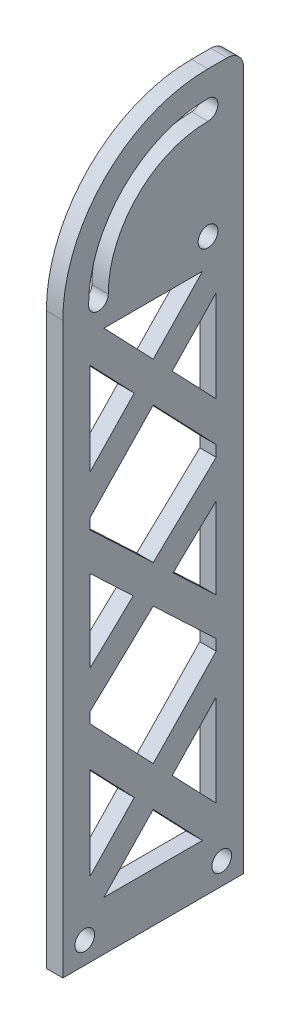
SolidWorks part; units mm, degrees
ref_plane "Front Plane" through (0, 0, 0) normal (0, 0, 1) x (1, 0, 0)
ref_plane "Top Plane" through (0, 0, 0) normal (0, 1, 0) x (1, 0, 0)
ref_plane "Right Plane" through (0, 0, 0) normal (1, 0, 0) x (0, 0, -1)
sketch "Sketch1" plane through (0, 0, 0) normal (1, 0, 0) x (0, 0, -1)
  line L0 (28, 103.9687) -> (33, 103.9687) construction
  line L1 (-14.1357, 103.9687) -> (0, 103.9687) construction
  line L2 (33, 103.9687) -> (33, 127.4687)
  line L3 (30, 130.4687) -> (26.5, 130.4687)
  line L4 (4, 4) -> (29, 4) construction
  line L5 (16.5, 4) -> (16.5, 0) construction
  line L7 (33, 103.9687) -> (33, 0)
  line L8 (33, 0) -> (0, 0)
  line L9 (0, 103.9687) -> (0, 0)
  circle A0 centre (4, 4) radius 1.5
  circle A1 centre (29, 4) radius 1.5
  circle A2 centre (26.5, 103.9687) radius 1.5
  arc A7 (0, 103.9687) -> (26.5, 130.4687) centre (26.5, 103.9687) cw
  arc A8 (33, 127.4687) -> (30, 130.4687) centre (30, 127.4687) ccw
  arc A9 (4.7, 103.9687) -> (26.5, 125.7687) centre (26.5, 103.9687) cw
  arc A10 (8.3, 103.9687) -> (26.5, 122.1687) centre (26.5, 103.9687) cw
  arc A11 (4.7, 103.9687) -> (8.3, 103.9687) centre (6.5, 103.9687) ccw
  arc A12 (26.5, 122.1687) -> (26.5, 125.7687) centre (26.5, 123.9687) ccw
  arc A13 (4.7, 103.9687) -> (26.5, 125.7687) centre (26.5, 103.9687) cw construction
  point P6 (0, 0)
  dimension "D1" = 3
  dimension "D2" = 3
  dimension "D4" = 3
  dimension "D6" = 4
  dimension "D12" = 3
  dimension "D9" = 3.6
  dimension "D11" = 20
  dimension "D3" = 4
  dimension "D5" = 100
  dimension "D10" = 5
  dimension "D15" = 33
extrude "Boss-Extrude1" add sketch "Sketch1" along normal blind 3
hole_wizard "M3 Clearance Hole1" positions "Sketch2" profile "Sketch3" hole size "M3" standard "ANSI Metric" end condition through all
sketch "Sketch2" plane through (0, 0, 0) normal (-1, 0, 0) x (0, 0, 1)
  point P0 (-29, 4)
  point P3 (-4, 4)
  point P6 (-26.5, 103.9687)
sketch "Sketch3" plane through (0, 4, -29) normal (0, 1, 0) x (0, 0, 1)
  line L0 (0, 0) -> (0, 3)
  line L1 (0, 3) -> (1.8, 3)
  line L2 (1.8, 3) -> (1.8, 0)
  line L5 (1.8, 0) -> (0, 0)
  line L11 (0, -6.35) -> (0, 107.95) construction
  dimension "Thru Hole Dia." = 3.6
  dimension "Thru Hole Depth" = 3
sketch "Sketch4" plane through (3, 0, 0) normal (1, 0, 0) x (0, 0, -1)
  line L6 (25.5, 9) -> (5, 30.4241)
  line L7 (0, 103.9687) -> (0, 0) construction
  line L8 (28, 13.6195) -> (5, 37.6562)
  line L39 (5, 98.9687) -> (28, 98.9687)
  line L40 (5, 98.9687) -> (5, 9)
  line L41 (5, 9) -> (28, 9)
  line L42 (28, 98.9687) -> (28, 9)
  line L43 (33, 0) -> (33, 127.4687) construction
  line L44 (7.5, 9) -> (28, 30.4241)
  line L45 (5, 13.6195) -> (28, 37.6562)
  line L46 (16.5, 25.6379) -> (20.1126, 22.1811) construction
  line L47 (12.8874, 22.1811) -> (16.5, 25.6379) construction
  line L48 (5, 39.6562) -> (28, 61.4277)
  line L49 (5, 46.5411) -> (28, 68.3125)
  line L50 (28, 39.6562) -> (5, 61.4277)
  line L51 (28, 46.5411) -> (5, 68.3125)
  line L52 (13.0628, 53.7956) -> (16.5, 57.4268) construction
  line L53 (19.9372, 53.7956) -> (16.5, 57.4268) construction
  line L54 (5, 39.6562) -> (28, 39.6562) construction
  line L55 (5, 37.6562) -> (28, 37.6562) construction
  line L56 (16.5, 37.6562) -> (16.5, 39.6562) construction
  line L57 (5, 70.3125) -> (28, 94.3492)
  line L58 (5, 77.5447) -> (25.5, 98.9687)
  line L59 (15.25, 88.2567) -> (18.8626, 84.7999) construction
  line L60 (28, 70.3125) -> (5, 94.3492)
  line L61 (28, 77.5447) -> (7.5, 98.9687)
  line L62 (17.75, 88.2567) -> (14.1374, 84.7999) construction
  line L63 (5, 70.3125) -> (28, 70.3125) construction
  line L64 (28, 68.3125) -> (5, 68.3125) construction
  line L65 (16.5, 70.3125) -> (16.5, 68.3125) construction
  line L66 (16.5, 98.9687) -> (16.5, 70.3125) construction
  line L67 (16.5, 68.3125) -> (16.5, 39.6562) construction
  line L68 (16.5, 37.6562) -> (16.5, 9) construction
  circle A4 centre (26.5, 103.9687) radius 1.8 construction
  circle A5 centre (29, 4) radius 1.8 construction
  circle A6 centre (4, 4) radius 1.8 construction
  circle A7 centre (26.5, 103.9687) radius 1.8 construction
  circle A8 centre (29, 4) radius 1.8 construction
  circle A9 centre (4, 4) radius 1.8 construction
  point P40 (16.5, 57.4268)
  point P43 (16.5, 57.4268)
  point P57 (24.4178, 9)
  point P59 (16.5, 35.4082)
  dimension "D1" = 5
  dimension "D2" = 5
  dimension "D3" = 5
  dimension "D4" = 5
  dimension "D5" = 5
  dimension "D6" = 2.5
  dimension "D7" = 2.5
  dimension "D8" = 2
extrude "Cut-Extrude1" cut sketch "Sketch4" against normal blind 10 contours L40 L45 L6 | L44 L41 L6 | L44 L8 L42 | L42 L50 L48 L40 L8 L45 | L51 L42 L48 | L49 L50 L40 | L42 L60 L57 L40 L51 L49 | L61 L42 L57 | L58 L60 L40 | L61 L58 L39
